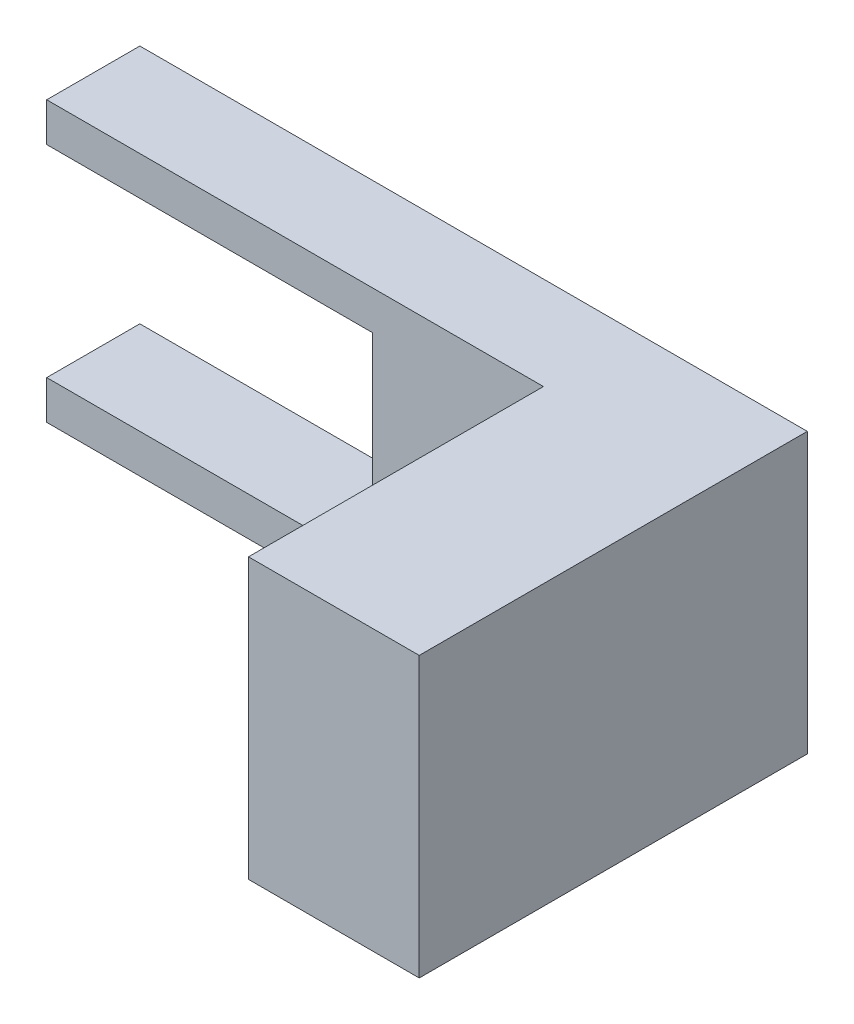
SolidWorks part; units mm, degrees
ref_plane "Front Plane" through (0, 0, 0) normal (0, 0, 1) x (1, 0, 0)
ref_plane "Top Plane" through (0, 0, 0) normal (0, 1, 0) x (1, 0, 0)
ref_plane "Right Plane" through (0, 0, 0) normal (1, 0, 0) x (0, 0, -1)
sketch "Sketch1" plane through (0, 0, 0) normal (0, 1, 0) x (1, 0, 0)
  line L0 (-10.3667, 24.3833) -> (32.6333, 24.3833)
  line L1 (32.6333, 24.3833) -> (32.6333, -0.6167)
  line L2 (32.6333, -0.6167) -> (21.6333, -0.6167)
  line L3 (21.6333, -0.6167) -> (21.6333, 18.3833)
  line L4 (21.6333, 18.3833) -> (-10.3667, 18.3833)
  line L5 (-10.3667, 18.3833) -> (-10.3667, 24.3833)
  dimension "D1" = 11
  dimension "D2" = 25
  dimension "D3" = 6
  dimension "D4" = 43
extrude "Boss-Extrude1" add sketch "Sketch1" along normal blind 18
sketch "Sketch2" plane through (0, 0, -18.3833) normal (0, 0, 1) x (1, 0, 0)
  line L0 (-10.3667, 18) -> (-10.3667, 0) construction
  line L1 (-31.3667, 2.5) -> (10.6333, 2.5)
  line L2 (-31.3667, 2.5) -> (-31.3667, 15.5)
  line L3 (-31.3667, 15.5) -> (10.6333, 15.5)
  line L4 (10.6333, 2.5) -> (10.6333, 15.5)
  line L5 (-31.3667, 2.5) -> (10.6333, 15.5) construction
  line L6 (-31.3667, 15.5) -> (10.6333, 2.5) construction
  point P0 (-10.3667, 9)
  dimension "D1" = 42
  dimension "D2" = 13
extrude "Cut-Extrude1" cut sketch "Sketch2" against normal through all
